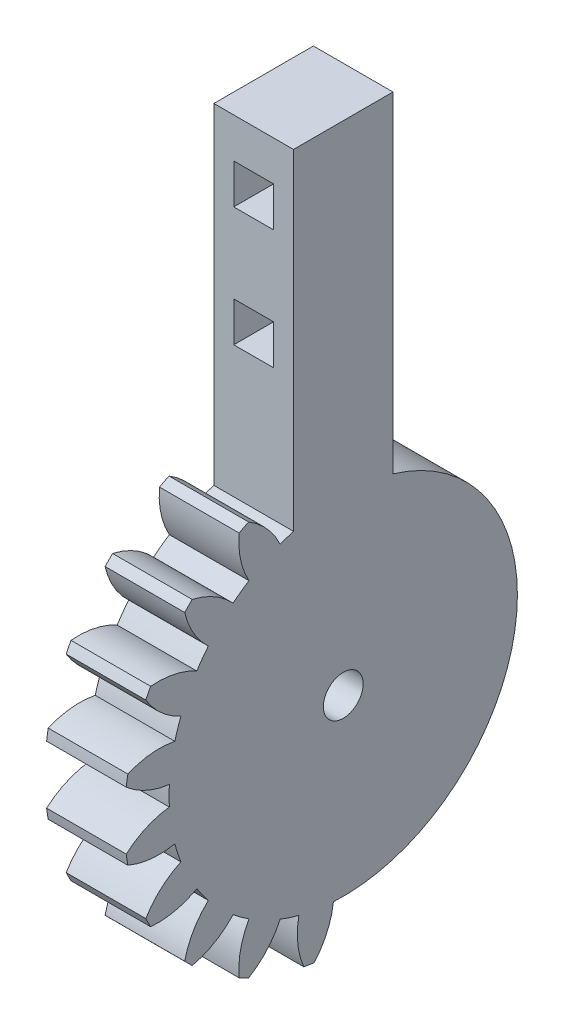
SolidWorks part; units mm, degrees
ref_plane "Plane1" through (0, 0, 0) normal (0, 0, 1) x (1, 0, 0)
ref_plane "Plane2" through (0, 0, 0) normal (0, 1, 0) x (1, 0, 0)
ref_plane "Plane3" through (0, 0, 0) normal (1, 0, 0) x (0, 0, -1)
other "Configuration Table"
sketch "HoldingSke" plane through (0, 0, 0) normal (0, 1, 0) x (1, 0, 0)
  line L0 (0, 0) -> (0.4698, -0.171)
  line L1 (-15, 0) -> (100, 0) construction
  line L2 (0, 0) -> (-2.1039, 2.3779)
  line L3 (0, 0) -> (-11.863, 4.5341)
  line L4 (0, 0) -> (8.1152, 2.9537)
  line L5 (0, 0) -> (-46.8476, -17.4728)
  line L6 (0, 0) -> (-8.2896, -5.593)
  line L7 (-2.1039, 2.3779) -> (8.6586, 51.2059)
  line L8 (-76.2, 54.61) -> (-75.5, 54.61)
  line L9 (-71.009, 38.7566) -> (-53.1078, 45.2721)
  line L10 (-76.2, 71.12) -> (104.1128, 71.12)
  line L11 (0, 0) -> (-10, 0)
  line L12 (-76.2, 101.6) -> (-76.133, 101.6)
  line L13 (24.9733, 27.94) -> (52.9518, 28.4284)
  line L14 (24.9733, 27.94) -> (24.9743, 27.94)
  line L15 (24.9733, 27.94) -> (100.4006, 29.5858)
  line L16 (-63.627, -2) -> (-12.827, -2)
  circle A0 centre (0, 0) radius 2
  circle A1 centre (0, 0) radius 17.499
  circle A2 centre (0, 0) radius 37.5
  circle A3 centre (0, 0) radius 2
  dimension "MHD" = 34.998
  dimension "Hub_dia" = 75
  dimension "Bore" = 4
  dimension "MBD" = 4
  dimension "Num_teeth" = 20
  dimension "Pitch" = 0.5
  dimension "Overall_len" = 50
  dimension "Show_teeth" = 20
  dimension "Thickness" = 10
  dimension "OAL" = 50.0001
  dimension "T_dim" = 0.7
  dimension "Ap" = 20
  dimension "H" = 19.05
  dimension "Pitch_radius" = 180.3128
  dimension "Width" = 10
  dimension "Backlash" = 0.067
  dimension "Addendum_fac" = 1
  dimension "Dedendum_fac" = 1.25
  dimension "Clearance_fac" = 0.25
  dimension "Dedendum_add" = 0.001
  dimension "Module" = 2
sketch "BasProSke" plane through (0, 0, 0) normal (0, 1, 0) x (1, 0, 0)
  line L0 (-10, 0) -> (60, 0) construction
  line L1 (0, 0) -> (0, 22)
  line L2 (0, 0) -> (10, 0)
  line L3 (10, 0) -> (10, 22)
  line L4 (10, 22) -> (0, 22)
  dimension "Thickness" = 10
  dimension "Diameter" = 44
revolve "Base-Revolve" add sketch "BasProSke" angle 360 about L0
sketch "TooCutSke" plane through (0, 0, 0) normal (1, 0, 0) x (0, 0, -1)
  line L1 (0, 0) -> (0, 107) construction
  line L2 (0, 0) -> (-1.6864, 19.9288) construction
  line L3 (0, 0) -> (-6.2409, 39.4033) construction
  line L4 (-1.6864, 19.9288) -> (-3.1204, 19.7016) construction
  arc A0 (0.9862, 17.4712) -> (-0.9862, 17.4712) centre (0, 0) ccw
  arc A1 (2.9329, 21.8293) -> (-2.9329, 21.8293) centre (0, 0) ccw
  circle A2 centre (0, 0) radius 20 construction
  circle A3 centre (0, 0) radius 18.7939 construction
  arc A4 (-0.9862, 17.4712) -> (-2.9329, 21.8293) centre (-8.9313, 16.536) ccw
  arc A5 (2.9329, 21.8293) -> (0.9862, 17.4712) centre (8.9313, 16.536) ccw
  dimension "Root_dia" = 34.998
  dimension "Overcut_dia" = 44.0508
  dimension "Pitch_dia" = 40
  dimension "Base_dia" = 37.5877
  dimension "Flank_rad" = 8
  dimension "Half_ang" = 9
  dimension "Half_CT" = 1.4519
extrude "ToothCut" cut sketch "TooCutSke" along normal through all
fillet "Breaks" [suppressed] radius 0.04
fillet "RootFillets" [suppressed] radius 0.501
pattern_circular "TeethCuts" count 20 every 18 about axis through (-10, 0, 0) along (1, 0, 0) of "ToothCut", "RootFillets", "Breaks"
sketch "HubNeaOneSke" plane through (0, 0, 0) normal (-1, 0, 0) x (0, 0, 1)
  circle A0 centre (0, 0) radius 17.499
  dimension "Diameter" = 34.998
extrude "HubNearOne" [suppressed] add sketch "HubNeaOneSke" along normal blind 40.0001
sketch "HubNeaBotSke" plane through (0, 0, 0) normal (-1, 0, 0) x (0, 0, 1)
  circle A0 centre (0, 0) radius 17.499
  dimension "Diameter" = 34.998
extrude "HubNearBoth" [suppressed] add sketch "HubNeaBotSke" along normal blind 20
ref_plane "FarPln" through (10, 0, 0) normal (1, 0, 0) x (0, 0, -1)
sketch "HubFarSke" plane through (10, 0, 0) normal (1, 0, 0) x (0, 0, -1)
  circle A0 centre (0, 0) radius 17.499
  dimension "Diameter" = 34.998
extrude "HubFar" [suppressed] add sketch "HubFarSke" along normal blind 20
sketch "BorSke" plane through (0, 0, 0) normal (1, 0, 0) x (0, 0, -1)
  circle A0 centre (0, 0) radius 2
  dimension "Diameter" = 4
extrude "Bore" cut sketch "BorSke" along normal mid plane 100.0001
sketch "KeySke" plane through (0, 0, 0) normal (1, 0, 0) x (0, 0, -1)
  line L0 (-0.8, 0) -> (-0.8, 2.7)
  line L1 (-0.8, 2.7) -> (0.8, 2.7)
  line L2 (0.8, 2.7) -> (0.8, 0)
  line L3 (0, 0) -> (0, 34) construction
  line L4 (-0.8, 0) -> (0.8, 0)
  dimension "Offset" = 2.7
  dimension "Width" = 1.6
extrude "Keyway" [suppressed] cut sketch "KeySke" along normal mid plane 100.0001
pattern_circular "Keyway2" [suppressed] count 2 every 90 about axis through (-10, 0, 0) along (1, 0, 0)
sketch "Sketch3" plane through (0, 0, 0) normal (-1, 0, 0) x (0, 0, 1)
  line L1 (-26.5812, 27.083) -> (-5.1039, 27.083)
  line L2 (-26.5812, 27.083) -> (-26.5812, -22.3044)
  line L3 (-26.5812, -22.3044) -> (-5.1039, -22.3044)
  line L4 (-5.1039, 27.083) -> (-5.1039, -22.3044)
  line L5 (0.8101, -22.3044) -> (-5.1039, -22.3044)
  line L6 (0.8101, -22.3044) -> (0.8101, -2.591)
  line L7 (0.8101, -2.591) -> (-5.1039, -2.591)
  line L9 (-0.9862, 17.4712) -> (0, 17.4712)
  line L10 (-0.9862, 17.4712) -> (-0.9862, 17.499)
  line L11 (-0.9862, 17.499) -> (0, 17.499)
  line L12 (0, 17.4712) -> (0, 17.499)
  line L13 (-5.1039, 27.083) -> (-0.4931, 27.083)
  line L15 (-5.1039, 10.6897) -> (-0.4931, 10.6897)
  line L16 (-0.4931, 27.083) -> (-0.4931, 10.6897)
  arc A0 (0.9862, 17.4712) -> (-0.9862, 17.4712) centre (0, 0) ccw construction
  arc A1 (-0.9862, 17.4712) -> (-2.9127, 21.8063) centre (-8.9313, 16.536) ccw construction
extrude "Cut-Extrude1" cut sketch "Sketch3" against normal up to surface (10 mm away) contours L4 L1 L2 L3 | L16 L13 L4 L15 L9 L10 L11 | L6 L7 L4 L5 up to face at (10, 0, 2)
sketch "Sketch4" plane through (0, 0, 0) normal (-1, 0, 0) x (0, 0, 1)
  circle A2 centre (0, 0) radius 2
  circle A3 centre (0, 0) radius 17.499
extrude "Boss-Extrude2" add sketch "Sketch4" against normal up to surface (10 mm away) contours A3
sketch "Sketch5" plane through (0, 0, 0) normal (-1, 0, 0) x (0, 0, 1)
  line L1 (-5, 0) -> (5, 0)
  line L2 (-5, 0) -> (-5, 50)
  line L3 (-5, 50) -> (5, 50)
  line L4 (5, 0) -> (5, 50)
  circle A1 centre (0, 0) radius 2 construction
  circle A2 centre (0, 0) radius 2
  point P4 (0, 0)
  arc M38 (6.3368, 16.3113) -> (4.461, 16.9208) centre (0, 0) ccw
  arc M39 (4.461, 16.9208) -> (3.9684, 21.6391) centre (-3.3843, 18.4866) ccw
  arc M40 (3.9684, 21.6391) -> (2.9127, 21.8063) centre (0, 0) ccw
  arc M41 (2.9127, 21.8063) -> (0.9862, 17.4712) centre (8.9313, 16.536) ccw
  arc M42 (0.9862, 17.4712) -> (0.9862, -17.4712) centre (0, 0) ccw
  circle M45 centre (0, 0) radius 2
  dimension "D1" = 10
  dimension "D2" = 50
extrude "Boss-Extrude3" add sketch "Sketch5" against normal up to surface (10 mm away) contours L4 L3 L2 M38 M42 M41 M40 M39 | L1 L4 L2 M38 M39 M40 M41 M42 M45
sketch "Sketch7" plane through (0, 0, 5) normal (0, 0, 1) x (1, 0, 0)
  line L0 (10, -21.8063) -> (0, -21.8063) construction
  line L1 (10, 50) -> (8, 50)
  line L2 (10, 50) -> (10, -21.8063)
  line L3 (10, -21.8063) -> (8, -21.8063)
  line L4 (8, 50) -> (8, -21.8063)
  dimension "D1" = 2
extrude "Cut-Extrude3" cut sketch "Sketch7" against normal through all both and the other way through all
sketch "Sketch6" plane through (0, 0, -5) normal (0, 0, -1) x (-1, 0, 0)
  line L0 (-6, 44) -> (-8, 44) construction
  line L1 (-6, 46) -> (-2, 46)
  line L2 (-6, 46) -> (-6, 42)
  line L3 (-6, 42) -> (-2, 42)
  line L4 (-2, 46) -> (-2, 42)
  line L5 (-6, 34) -> (-2, 34)
  line L6 (-6, 34) -> (-6, 30)
  line L7 (-6, 30) -> (-2, 30)
  line L8 (-2, 34) -> (-2, 30)
  line L10 (-2, 44) -> (0, 44) construction
  line L11 (0, 16.7695) -> (0, 50) construction
  line L12 (-8, 50) -> (0, 50) construction
  line L13 (-8, 50) -> (-8, 16.7695) construction
  point P10 (0, 0)
  point P18 (-10, 44)
  dimension "D1" = 4
  dimension "D2" = 8
  dimension "D3" = 4
extrude "Cut-Extrude5" cut sketch "Sketch6" against normal through all contours L6 L5 L8 L7 | L2 L1 L4 L3
equation "' \"Module@HoldingSke\" = 6.35"
equation "' \"Num_teeth@HoldingSke\" = 12"
equation "' \"Ap@HoldingSke\" =  20"
equation "' \"Ap@HoldingSke\" = 20"
equation "' \"Width@HoldingSke\" = 0.5 * 25.4"
equation "' \"Hub_dia@HoldingSke\"= 1 * 25.4"
equation "' \"Hub_dia@HoldingSke\" = 1 * 25.4"
equation "' \"Overall_len@HoldingSke\" = 1.0 * 25.4"
equation "' \"Bore@HoldingSke\" = 0.75 * 25.4"
equation "' \"T_dim@HoldingSke\" = 0.1 * 25.4"
equation "' \"Width@KeySke\" = 0.25 * 25.4"
equation "' \"Show_teeth@HoldingSke\" = 13"
equation "' \"Backlash@HoldingSke\" = 0.009 * 25.4"
equation "' \"Addendum_fac@HoldingSke\" = 1.0"
equation "' \"Dedendum_fac@HoldingSke\" = 1.25"
equation "' \"Dedendum_add@HoldingSke\" = 0.00005 * 25.4"
equation "' \"Clearance_fac@HoldingSke\" = 0.25"
equation "\"Pitch@HoldingSke\" = 1 / \"Module@HoldingSke\""
equation "\"Overcut_dia@TooCutSke\" = (\"Num_teeth@HoldingSke\" + 2 * \"Addendum_fac@HoldingSke\") / \"Pitch@HoldingSke\" + 0.002 * 25.4"
equation "\"Pitch_dia@TooCutSke\" = \"Num_teeth@HoldingSke\" / \"Pitch@HoldingSke\""
equation "\"Base_dia@TooCutSke\" = \"Num_teeth@HoldingSke\" / \"Pitch@HoldingSke\" * cos((\"Ap@HoldingSke\"  * 3.14159265 / 180))"
equation "\"Root_dia@TooCutSke\" = (\"Num_teeth@HoldingSke\" + 2) / \"Pitch@HoldingSke\" - 2 * (\"Addendum_fac@HoldingSke\" + \"Dedendum_fac@HoldingSke\") / \"Pitch@HoldingSke\" - \"Dedendum_add@HoldingSke\" * 2"
equation "\"Half_ang@TooCutSke\" = 180 / \"Num_teeth@HoldingSke\""
equation "\"Half_CT@TooCutSke\" = \"Num_teeth@HoldingSke\" / \"Pitch@HoldingSke\" * sin((3.14159265 / 2 / \"Num_teeth@HoldingSke\")) / 2 - 7 * \"Backlash@HoldingSke\" / 4"
equation "\"Flank_rad@TooCutSke\" = \"Num_teeth@HoldingSke\" / \"Pitch@HoldingSke\" / 5"
equation "\"Radius@RootFillets\" = \"Clearance_fac@HoldingSke\" / \"Pitch@HoldingSke\" + \"Dedendum_add@HoldingSke\""
equation "\"Break_rad@Breaks\" = 0.02 / \"Pitch@HoldingSke\""
equation "\"Thickness@HoldingSke\" = \"Width@HoldingSke\""
equation "\"OAL@HoldingSke\" = \"Thickness@HoldingSke\""
equation "\"MHD@HoldingSke\" = (\"Num_teeth@HoldingSke\" + 2) / \"Pitch@HoldingSke\" - 2 * (\"Addendum_fac@HoldingSke\" + \"Dedendum_fac@HoldingSke\")  / \"Pitch@HoldingSke\" - \"Dedendum_add@HoldingSke\" * 2"
equation "\"MBD@HoldingSke\" = (\"Num_teeth@HoldingSke\" + 2) / \"Pitch@HoldingSke\" - 2 * (\"Addendum_fac@HoldingSke\" + \"Dedendum_fac@HoldingSke\")  / \"Pitch@HoldingSke\" - \"Dedendum_add@HoldingSke\" * 2 - 0.002 * 25.4"
equation "\"MHD@HoldingSke\" = ((sgn( \"MHD@HoldingSke\" - \"Hub_dia@HoldingSke\" )-1)*( \"MHD@HoldingSke\" - \"Hub_dia@HoldingSke\" ))/-2+ \"Hub_dia@HoldingSke\""
equation "\"MBD@HoldingSke\" = ((sgn( \"MBD@HoldingSke\" - \"Bore@HoldingSke\" )-1)*( \"MBD@HoldingSke\" - \"Bore@HoldingSke\" ))/-2+ \"Bore@HoldingSke\""
equation "\"OAL@HoldingSke\" = ((sgn( \"OAL@HoldingSke\" - \"Overall_len@HoldingSke\" )+1)*( \"OAL@HoldingSke\" - \"Overall_len@HoldingSke\" ))/2 + \"Overall_len@HoldingSke\" + 0.000002 * 25.4"
equation "\"Num_teeth@TeethCuts\" = int( \"Show_teeth@HoldingSke\" ) + 1"
equation "\"Num_teeth@TeethCuts\" = ((sgn( \"Num_teeth@TeethCuts\" - \"Num_teeth@HoldingSke\" )-1)*( \"Num_teeth@TeethCuts\" - \"Num_teeth@HoldingSke\" ))/-2+ \"Num_teeth@HoldingSke\""
equation "\"Num_teeth@TeethCuts\" = ((sgn( \"Num_teeth@TeethCuts\" - 2.0)+1)*( \"Num_teeth@TeethCuts\" - 2.0))/2 +2.0"
equation "\"Angle@TeethCuts\" = 360.0 / \"Num_teeth@HoldingSke\""
equation "\"Diameter@BasProSke\" = (\"Num_teeth@HoldingSke\" + 2 * \"Addendum_fac@HoldingSke\") / \"Pitch@HoldingSke\""
equation "\"Thickness@BasProSke\"  = \"Thickness@HoldingSke\""
equation "' \"Fillet_rad@BasProSke\" =  \"Thickness@HoldingSke\" * 0.05"
equation "' \"Fillet_rad@BasProSke\" = \"Thickness@HoldingSke\" * 0.05"
equation "\"MHD@HoldingSke\" = ((sgn( \"MHD@HoldingSke\" - \"Root_dia@TooCutSke\" )-1)*( \"MHD@HoldingSke\" - \"Root_dia@TooCutSke\" ))/-2+ \"Root_dia@TooCutSke\""
equation "\"Diameter@HubNeaOneSke\" = \"MHD@HoldingSke\""
equation "\"Length@HubNearOne\" = \"OAL@HoldingSke\" - \"Thickness@BasProSke\""
equation "\"Diameter@HubNeaBotSke\" = \"MHD@HoldingSke\""
equation "\"Length@HubNearBoth\" = ( \"OAL@HoldingSke\" - \"Thickness@BasProSke\" ) / 2.0"
equation "\"Thickness@FarPln\" = \"Thickness@BasProSke\""
equation "\"Diameter@HubFarSke\" = \"MHD@HoldingSke\""
equation "\"Length@HubFar\" = ( \"OAL@HoldingSke\" - \"Thickness@BasProSke\" ) / 2.0"
equation "\"Diameter@BorSke\" = \"MBD@HoldingSke\""
equation "\"D1@Bore\" = \"OAL@HoldingSke\" * 2.0"
equation "\"D1@Keyway\" = \"OAL@HoldingSke\" * 2.0"
equation "\"Offset@KeySke\" = \"T_dim@HoldingSke\" + \"MBD@HoldingSke\" / 2.0"
